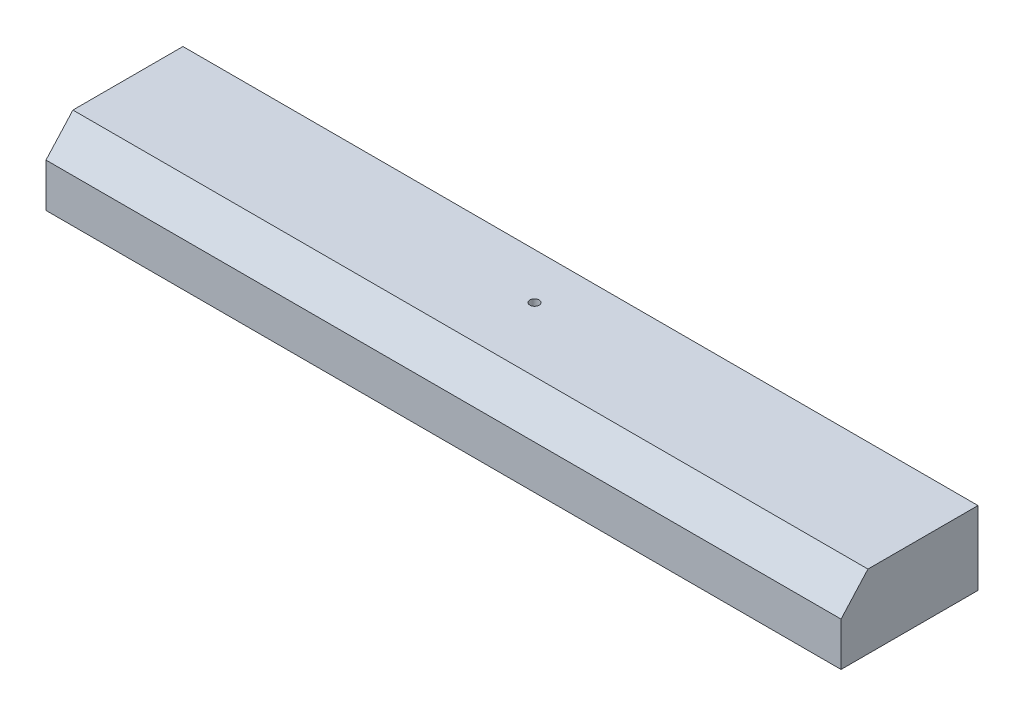
SolidWorks part; units mm, degrees
ref_plane "Front Plane" through (0, 0, 0) normal (0, 0, 1) x (1, 0, 0)
ref_plane "Top Plane" through (0, 0, 0) normal (0, 1, 0) x (1, 0, 0)
ref_plane "Right Plane" through (0, 0, 0) normal (1, 0, 0) x (0, 0, -1)
sketch "Sketch1" plane through (0, 0, 0) normal (1, 0, 0) x (0, 0, -1)
  line L0 (0, 0) -> (0, -37) construction
  line L1 (0, -37) -> (55, -37) construction
  line L2 (55, -37) -> (0, 0) construction
  line L3 (55, -37) -> (0, 24.0837) construction
  line L4 (0, 24.0837) -> (0, 0) construction
  line L5 (0, -37) -> (-55, -37) construction
  line L6 (-55, -37) -> (0, 0) construction
  line L7 (-55, -37) -> (0, 24.0837) construction
  dimension "D1" = 37
  dimension "D2" = 55
  dimension "D3" = 48
ref_plane "Plane1" through (0, 0, 0) normal (0, 1, 0) x (1, 0, 0)
sketch "Sketch2" plane through (0, 0, 0) normal (0, 1, 0) x (1, 0, 0)
  line L0 (-81.5, 0) -> (81.5, 0)
  line L1 (0, 17.8) -> (0, 0) construction
  line L2 (0, 0) -> (0, 55) construction
  line L3 (-40, 17.8) -> (40, 17.8) construction
  line L4 (-86.5, -7) -> (86.5, -7)
  line L5 (86.5, -7) -> (86.5, 22.8)
  line L6 (86.5, 22.8) -> (-86.5, 22.8)
  line L7 (-86.5, 22.8) -> (-86.5, -7)
  spline S0 degree 3 poles (-81.5, 0) (-74.4361, 13.8819) (-43.2594, 16.3622) (0, 18.5559) (43.2594, 16.3622) (74.4361, 13.8819) (81.5, 0) knots 0 0 0 0 0.237126 0.5 0.762874 1 1 1 1
  point P2 (0, 0)
  point P12 (0, 17.8)
  dimension "D1" = 163
  dimension "D2" = 80
  dimension "D3" = 17.8
  dimension "D4" = 10
  dimension "D5" = 10.5
  dimension "D6" = 36
  dimension "D7" = 16
  dimension "D8" = 10
  dimension "D9" = 36
  dimension "D10" = 7
  dimension "D11" = 5
  dimension "D12" = 5
  dimension "D13" = 5
extrude "Boss-Extrude1" add sketch "Sketch2" along normal blind 14
sketch "Sketch4" plane through (0, 14, 0) normal (0, 1, 0) x (1, 0, 0)
  line L0 (-86.5, 22.8) -> (86.5, 22.8)
  line L1 (86.5, 22.8) -> (86.5, -7)
  line L2 (86.5, -7) -> (-86.5, -7)
  line L3 (-86.5, -7) -> (-86.5, 22.8)
  line L4 (0, 0) -> (0, 55) construction
  line L5 (0, 13.8) -> (0, 17.8) construction
  circle A0 centre (0, 12.8) radius 1
  spline S0 degree 3 poles (81.5, 0) (74.4361, 13.8819) (43.2594, 16.3622) (0, 18.5559) (-43.2594, 16.3622) (-74.4361, 13.8819) (-81.5, 0) knots 0 0 0 0 0.237126 0.5 0.762874 1 1 1 1 construction
  dimension "D1" = 2
  dimension "D2" = 4
extrude "Boss-Extrude3" add sketch "Sketch4" along normal blind 2
sketch "Sketch5" plane through (0, 14, 0) normal (0, -1, 0) x (1, 0, 0)
  line L0 (0, -9.8) -> (-7.9313, -17.7313)
  line L1 (0, -55) -> (0, 0) construction
  line L2 (-7.9313, -17.7313) -> (-7.9313, -22.8)
  line L3 (86.5, -22.8) -> (-86.5, -22.8) construction
  line L4 (-7.9313, -22.8) -> (7.9313, -22.8)
  line L5 (7.9313, -22.8) -> (7.9313, -17.7313)
  line L6 (7.9313, -17.7313) -> (0, -9.8)
  line L7 (0, -17.8) -> (0, -22.8) construction
  line L8 (0.7071, -13.5071) -> (-1.5, -11.3) construction
  line L9 (0, -13.8) -> (0, -11.8) construction
  circle A1 centre (0, -12.8) radius 1 construction
  circle A2 centre (0, -12.8) radius 1
  spline S0 degree 3 poles (81.5, 0) (74.4361, -13.8819) (43.2594, -16.3622) (0, -18.5559) (-43.2594, -16.3622) (-74.4361, -13.8819) (-81.5, 0) knots 0 0 0 0 0.237126 0.5 0.762874 1 1 1 1 construction
  point P17 (0, -12.8)
  dimension "D1" = 8
  dimension "D2" = 45
extrude "Boss-Extrude4" add sketch "Sketch5" along normal blind 5.5
sketch "Sketch3" plane through (0, 0, 0) normal (1, 0, 0) x (0, 0, -1)
  line L0 (-48.8688, -37) -> (4.9962, 22.8232)
  line L1 (-7, 0) -> (-7, 9.5) construction
  line L2 (-7, 16) -> (-7, 0) construction
  line L5 (-55, -37) -> (0, 24.0837) construction
  line L6 (0, -37) -> (-55, -37) construction
  line L7 (4.9962, 22.8232) -> (1.2805, 26.1688)
  line L8 (1.2805, 26.1688) -> (-52.5845, -33.6543)
  line L9 (-52.5845, -33.6543) -> (-48.8688, -37)
  dimension "D1" = 9.5
  dimension "D2" = 80.5
  dimension "D3" = 5
extrude "Cut-Extrude1" cut sketch "Sketch3" against normal through all both and the other way through all
